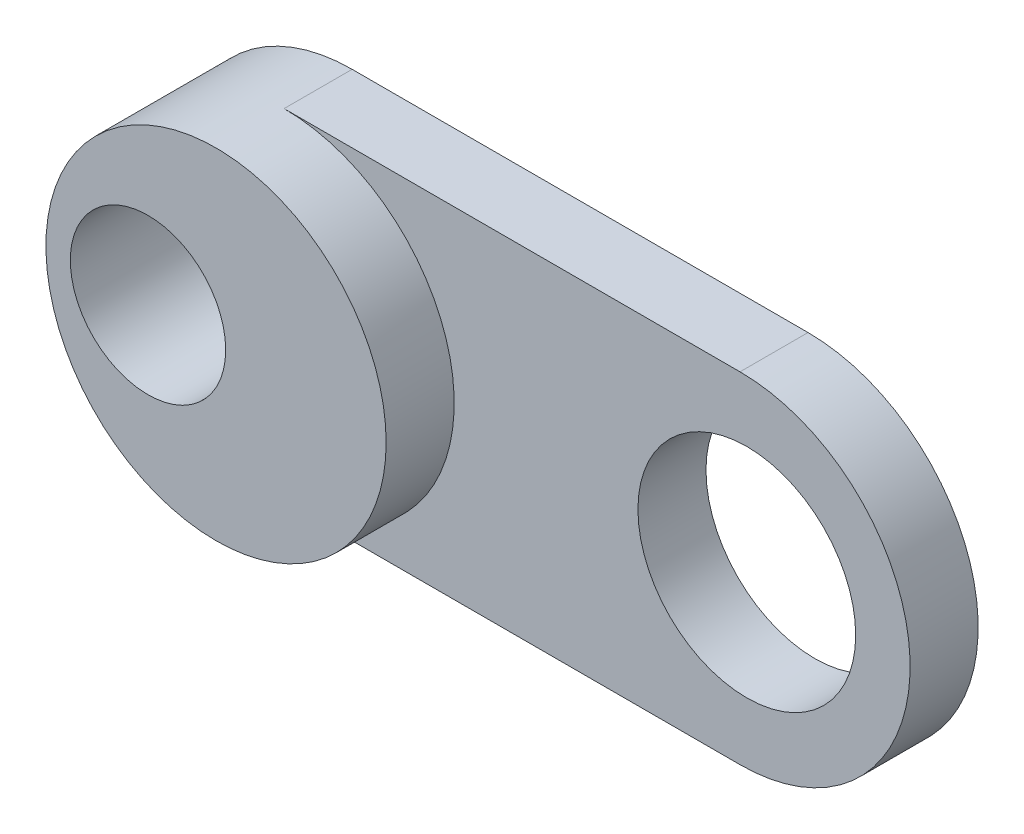
SolidWorks part; units mm, degrees
material "Custom Plastic"
ref_plane "Front Plane" through (0, 0, 0) normal (0, 0, 1) x (1, 0, 0)
ref_plane "Top Plane" through (0, 0, 0) normal (0, 1, 0) x (1, 0, 0)
ref_plane "Right Plane" through (0, 0, 0) normal (1, 0, 0) x (0, 0, -1)
sketch "Sketch1" plane through (0, 0, 0) normal (0, 0, 1) x (1, 0, 0)
  line L0 (0, 12.7) -> (17.018, 12.7)
  line L1 (0, 0) -> (17.018, 0)
  arc A0 (0, 0) -> (0, 12.7) centre (0, 6.35) cw
  arc A1 (17.018, 12.7) -> (17.018, 0) centre (17.018, 6.35) cw
  circle A2 centre (-2.54, 6.35) radius 2.9
  circle A3 centre (17.272, 6.35) radius 4.064
  dimension "D1" = 6.35
  dimension "D2" = 17.018
  dimension "D3" = 5.8
  dimension "D4" = 2.54
  dimension "D7" = 8.128
  dimension "D5" = 0.254
  dimension "D6" = 6.35
extrude "Boss-Extrude1" add sketch "Sketch1" along normal blind 2.54
sketch "Sketch2" plane through (0, 0, 2.54) normal (0, 0, 1) x (1, 0, 0)
  circle A0 centre (0, 6.35) radius 6.35
  arc A1 (0, 12.7) -> (0, 0) centre (0, 6.35) ccw construction
  arc M2 (0, 12.7) -> (0, 0) centre (0, 6.35) ccw
  circle M7 centre (-2.54, 6.35) radius 2.9
extrude "Boss-Extrude2" add sketch "Sketch2" along normal blind 2.54 contours A0 M2 M7
sketch "Sketch3" plane through (0, 0, 5.08) normal (0, 0, 1) x (1, 0, 0)
  line L0 (-2.9035, 3.4729) -> (-2.54, 3.55)
  line L1 (-2.54, 3.55) -> (-2.1765, 3.4729)
  line L4 (-2.54, 9.25) -> (-2.54, 3.45) construction
  line L5 (-3.2363, 3.638) -> (-2.9035, 3.4729)
  line L6 (-3.6076, 3.6536) -> (-3.2363, 3.638)
  line L7 (-3.8889, 3.8963) -> (-3.6076, 3.6536)
  line L8 (-4.2446, 4.0039) -> (-3.8889, 3.8963)
  line L9 (-4.4567, 4.3089) -> (-4.2446, 4.0039)
  line L10 (-4.7745, 4.5015) -> (-4.4567, 4.3089)
  line L11 (-4.9041, 4.8497) -> (-4.7745, 4.5015)
  line L12 (-5.164, 5.1152) -> (-4.9041, 4.8497)
  line L13 (-5.203, 5.4848) -> (-5.164, 5.1152)
  line L14 (-5.3886, 5.8066) -> (-5.203, 5.4848)
  line L15 (-5.3345, 6.1742) -> (-5.3886, 5.8066)
  line L16 (-5.4343, 6.5321) -> (-5.3345, 6.1742)
  line L17 (-5.2904, 6.8747) -> (-5.4343, 6.5321)
  line L18 (-5.2981, 7.2461) -> (-5.2904, 6.8747)
  line L19 (-5.0735, 7.5422) -> (-5.2981, 7.2461)
  line L20 (-4.9886, 7.9039) -> (-5.0735, 7.5422)
  line L21 (-4.6974, 8.1348) -> (-4.9886, 7.9039)
  line L22 (-4.5252, 8.464) -> (-4.6974, 8.1348)
  line L23 (-4.1858, 8.6152) -> (-4.5252, 8.464)
  line L24 (-3.9371, 8.8913) -> (-4.1858, 8.6152)
  line L25 (-3.5707, 8.9534) -> (-3.9371, 8.8913)
  line L26 (-3.2612, 9.1589) -> (-3.5707, 8.9534)
  line L27 (-2.8909, 9.1279) -> (-3.2612, 9.1589)
  line L28 (-2.54, 9.25) -> (-2.8909, 9.1279)
  line L29 (-2.1891, 9.1279) -> (-2.54, 9.25)
  line L30 (-1.8188, 9.1589) -> (-2.1891, 9.1279)
  line L31 (-1.5093, 8.9534) -> (-1.8188, 9.1589)
  line L32 (-1.1429, 8.8913) -> (-1.5093, 8.9534)
  line L33 (-0.8942, 8.6152) -> (-1.1429, 8.8913)
  line L34 (-0.5548, 8.464) -> (-0.8942, 8.6152)
  line L35 (-0.3826, 8.1348) -> (-0.5548, 8.464)
  line L36 (-0.0914, 7.9039) -> (-0.3826, 8.1348)
  line L37 (-0.0065, 7.5422) -> (-0.0914, 7.9039)
  line L38 (0.2181, 7.2461) -> (-0.0065, 7.5422)
  line L39 (0.2104, 6.8747) -> (0.2181, 7.2461)
  line L40 (0.3543, 6.5321) -> (0.2104, 6.8747)
  line L41 (0.2545, 6.1742) -> (0.3543, 6.5321)
  line L42 (0.3086, 5.8066) -> (0.2545, 6.1742)
  line L43 (0.123, 5.4848) -> (0.3086, 5.8066)
  line L44 (0.084, 5.1152) -> (0.123, 5.4848)
  line L45 (-0.1759, 4.8497) -> (0.084, 5.1152)
  line L46 (-0.3055, 4.5015) -> (-0.1759, 4.8497)
  line L47 (-0.6233, 4.3089) -> (-0.3055, 4.5015)
  line L48 (-0.8354, 4.0039) -> (-0.6233, 4.3089)
  line L49 (-1.1911, 3.8963) -> (-0.8354, 4.0039)
  line L50 (-1.4724, 3.6536) -> (-1.1911, 3.8963)
  line L51 (-1.8437, 3.638) -> (-1.4724, 3.6536)
  line L52 (-2.1765, 3.4729) -> (-1.8437, 3.638)
  circle A0 centre (-2.54, 6.35) radius 2.9 construction
  circle A1 centre (-2.54, 6.35) radius 2.8 construction
  point P83 (-2.54, 6.35)
  circle M5 centre (-2.54, 6.35) radius 2.9
  dimension "D2" = 5.6
  dimension "D1" = 25
extrude "Boss-Extrude3" [suppressed] add sketch "Sketch3" against normal up to surface (5.08 mm away) contours L22 L21 M5 | L20 L19 M5 | L18 L17 M5 | L16 L15 M5 | L14 L13 M5 | L12 L11 M5 | L10 L9 M5 | L8 L7 M5 | L6 L5 M5 | L1 L0 M5 | L52 L51 M5 | L50 L49 M5 | L48 L47 M5 | L46 L45 M5 | L44 L43 M5 | L42 L41 M5 | L40 L39 M5 | L38 L37 M5 | L36 L35 M5 | L34 L33 M5 | L32 L31 M5 | L30 L29 M5 | L28 L27 M5 | L26 L25 M5 | L24 L23 M5
